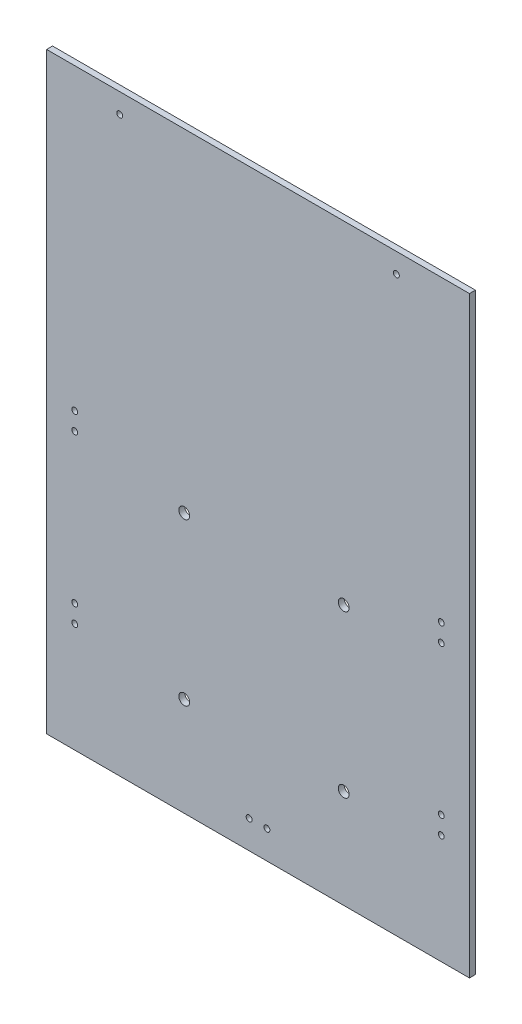
SolidWorks part; units mm, degrees
ref_plane "Front Plane" through (0, 0, 0) normal (0, 0, 1) x (1, 0, 0)
ref_plane "Top Plane" through (0, 0, 0) normal (0, 1, 0) x (1, 0, 0)
ref_plane "Right Plane" through (0, 0, 0) normal (1, 0, 0) x (0, 0, -1)
sketch "Sketch1" plane through (0, 0, 0) normal (0, 0, 1) x (1, 0, 0)
  line L1 (-102, -150) -> (102, -150)
  line L2 (-102, -150) -> (-102, 150)
  line L3 (-102, 150) -> (102, 150)
  line L4 (102, -150) -> (102, 150)
  line L5 (-102, -150) -> (102, 150) construction
  line L6 (-102, 150) -> (102, -150) construction
  point P0 (0, 0)
  dimension "D1" = 204
  dimension "D2" = 300
extrude "Boss-Extrude1" add sketch "Sketch1" along normal blind 3
sketch "Sketch2" plane through (0, 0, 3) normal (0, 0, 1) x (1, 0, 0)
  line L1 (-37.3469, -100) -> (43.3469, -100)
  line L2 (-37.3469, -100) -> (-37.3469, -18.3222)
  line L3 (-37.3469, -18.3222) -> (43.3469, -18.3222)
  line L4 (102, -150) -> (102, 150)
  line L5 (102, 150) -> (-102, 150)
  line L6 (-102, 150) -> (-102, -150)
  line L7 (-102, -150) -> (102, -150)
  line L8 (102, -150) -> (102, 150)
  line L9 (102, 150) -> (-102, 150)
  line L10 (-102, 150) -> (-102, -150)
  line L11 (-102, -150) -> (102, -150)
  line L12 (43.3469, -100) -> (43.3469, -18.3222)
  line L13 (-37.3469, -100) -> (43.3469, -18.3222) construction
  line L14 (-37.3469, -18.3222) -> (43.3469, -100) construction
  circle A0 centre (-37.3469, -18.3222) radius 2.75
  circle A1 centre (43.3469, -18.3222) radius 2.75
  circle A2 centre (43.3469, -100) radius 2.75
  circle A3 centre (-37.3469, -100) radius 2.75
  point P2 (3, -59.1611)
  dimension "D4" = 5.5
  dimension "D2" = 50
  dimension "D3" = 105
  dimension "D1" = 0
extrude "Cut-Extrude1" cut sketch "Sketch2" against normal blind 3 contours A0 | A1 | A2 | A3
sketch "Sketch4" plane through (-102, 0, 0) normal (-1, 0, 0) x (0, 0, 1)
  line L4 (0, 150) -> (0, -150)
  line L5 (0, -150) -> (3, -150)
  line L6 (3, -150) -> (3, 150)
  line L7 (3, 150) -> (0, 150)
  line L8 (0, 150) -> (0, -150)
  line L9 (0, -150) -> (3, -150)
  line L10 (3, -150) -> (3, 150)
  line L11 (3, 150) -> (0, 150)
  dimension "D1" = 0
extrude "Boss-Extrude2" add sketch "Sketch4" along normal blind 5
sketch "Sketch5" plane through (102, 0, 0) normal (1, 0, 0) x (0, 0, -1)
  line L4 (0, -150) -> (0, 150)
  line L5 (0, 150) -> (-3, 150)
  line L6 (-3, 150) -> (-3, -150)
  line L7 (-3, -150) -> (0, -150)
  line L8 (0, -150) -> (0, 150)
  line L9 (0, 150) -> (-3, 150)
  line L10 (-3, 150) -> (-3, -150)
  line L11 (-3, -150) -> (0, -150)
  dimension "D1" = 0
extrude "Boss-Extrude3" add sketch "Sketch5" along normal blind 5
sketch "Sketch3" plane through (0, 0, 3) normal (0, 0, 1) x (1, 0, 0)
  line L0 (102, -150) -> (102, 150)
  line L1 (-102, -150) -> (102, -150)
  line L2 (-102, 150) -> (-102, -150)
  line L3 (102, 150) -> (-102, 150)
  line L4 (107, -150) -> (107, 150)
  line L5 (107, 150) -> (-107, 150)
  line L6 (107, -150) -> (107, 150)
  line L7 (-107, -150) -> (107, -150)
  line L9 (107, 150) -> (-107, 150)
  line L11 (-107, -150) -> (107, -150)
  line L12 (0, -150) -> (0, -262.1425)
  line L13 (102, 150) -> (102, -150)
  line L14 (-102, -150) -> (-102, 150)
  line L20 (-107, 150) -> (-107, -150)
  line L21 (-107, 150) -> (-107, -150)
  circle A0 centre (92.747, -10.2538) radius 1.5
  circle A1 centre (92.747, -1.2538) radius 1.5
  circle A2 centre (92.747, -94.6187) radius 1.5
  circle A3 centre (92.747, -85.6187) radius 1.5
  circle A4 centre (-92.747, -85.6187) radius 1.5
  circle A5 centre (-92.747, -94.6187) radius 1.5
  circle A6 centre (-92.747, -1.2538) radius 1.5
  circle A7 centre (-92.747, -10.2538) radius 1.5
  dimension "D1" = 0
extrude "Cut-Extrude2" cut sketch "Sketch3" against normal blind 10 contours A2 | A3 | A4 | A5 | A6 | A7 | A1 | A0
sketch "Sketch9" plane through (0, 0, 3) normal (0, 0, 1) x (1, 0, 0)
  line L0 (-107, -150) -> (107, -150)
  line L1 (107, -150) -> (107, 150)
  line L2 (107, 150) -> (-107, 150)
  line L3 (-107, 150) -> (-107, -150)
  line L8 (-107, -150) -> (107, -150)
  line L9 (107, -150) -> (107, 150)
  line L10 (107, 150) -> (-107, 150)
  line L11 (-107, 150) -> (-107, -150)
  line L12 (-107, -150) -> (107, -150)
  line L13 (107, -150) -> (107, 150)
  line L14 (107, 150) -> (-107, 150)
  line L15 (-107, 150) -> (-107, -150)
  circle A0 centre (-4.5, -135.747) radius 1.5
  circle A1 centre (4.5, -135.747) radius 1.5
  circle A2 centre (43.3469, -100) radius 2.75
  circle A3 centre (-37.3469, -100) radius 2.75
  circle A4 centre (-37.3469, -18.3222) radius 2.75
  circle A5 centre (43.3469, -18.3222) radius 2.75
  dimension "D1" = 0
extrude "Cut-Extrude3" cut sketch "Sketch9" against normal blind 10 contours A0 | A1
sketch "Sketch10" plane through (0, 0, 3) normal (0, 0, 1) x (1, 0, 0)
  line L0 (97, 140) -> (-97, 140)
  line L1 (-97, 140) -> (-97, -140)
  line L2 (-97, -140) -> (97, -140)
  line L3 (97, -140) -> (97, 140)
  line L4 (-107, -150) -> (107, -150)
  line L5 (107, -150) -> (107, 150)
  line L6 (107, 150) -> (-107, 150)
  line L7 (-107, 150) -> (-107, -150)
  line L8 (-107, -150) -> (107, -150)
  line L9 (107, -150) -> (107, 150)
  line L10 (107, 150) -> (-107, 150)
  line L11 (-107, 150) -> (-107, -150)
  line L12 (0, 150) -> (0, 85.8496) construction
  line L13 (-70, 150) -> (-70, 85.8496)
  line L14 (70, 150) -> (70, 85.8496)
  circle A0 centre (-70, 140) radius 1.5
  circle A1 centre (70, 140) radius 1.5
  dimension "D1" = 0
  dimension "D2" = 10
  dimension "D3" = 70
  dimension "D4" = 70
extrude "Cut-Extrude4" cut sketch "Sketch10" against normal blind 10 contours L13 A0 L0 | L0 A0 L13 | L13 A0 L0 | L0 A0 L13 | A1 L0 L14 | A1 L14 L0 | A1 L0 L14 | A1 L14 L0
